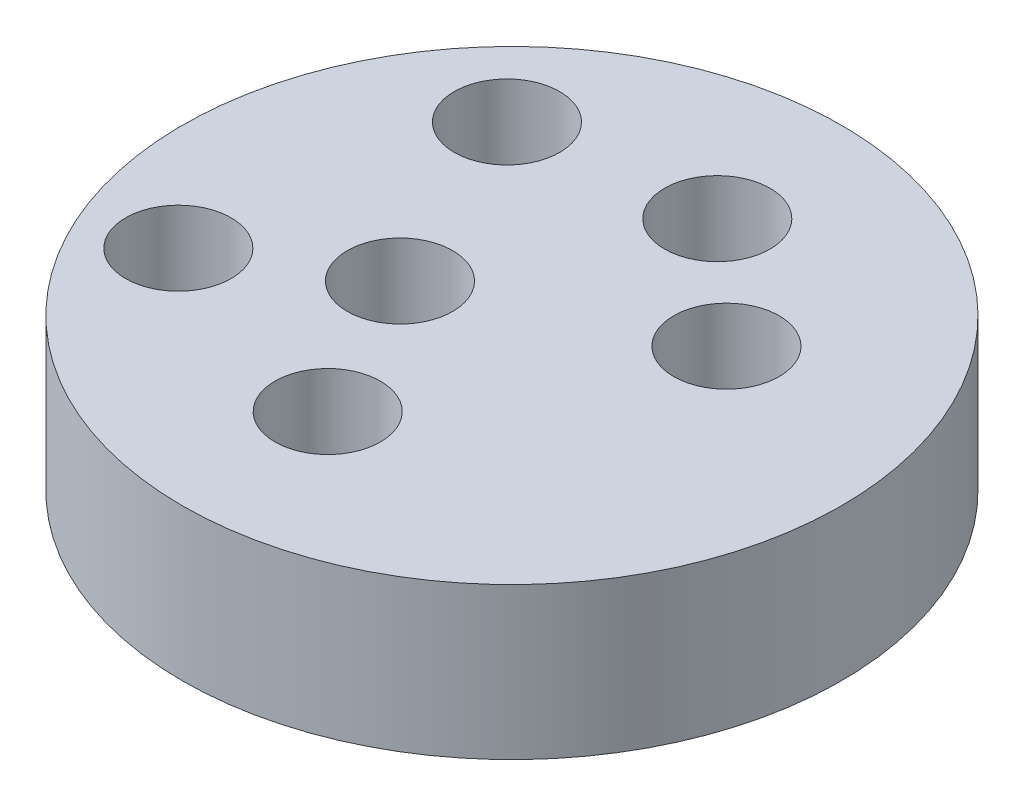
SolidWorks part; units mm, degrees
ref_plane "Front Plane" through (0, 0, 0) normal (0, 0, 1) x (1, 0, 0)
ref_plane "Top Plane" through (0, 0, 0) normal (0, 1, 0) x (1, 0, 0)
ref_plane "Right Plane" through (0, 0, 0) normal (1, 0, 0) x (0, 0, -1)
sketch "Sketch2" plane through (0, 0, 0) normal (0, 1, 0) x (1, 0, 0)
  circle A0 centre (0, 0) radius 50
  dimension "D1" = 100
extrude "Boss-Extrude2" add sketch "Sketch2" along normal blind 23
hole_wizard "Ø16.0mm Dowel Hole1" positions "Sketch5" profile "Sketch6" hole size "Ø16.0" standard "DIN" end condition through all
sketch "Sketch5" plane through (0, 23, 0) normal (0, 1, 0) x (1, 0, 0)
  point P0 (-34.1473, -16.4608)
  point P2 (-25.8045, 25.0499)
  point P4 (-1.359, -26.5937)
  point P6 (20.3005, 12.2433)
  point P8 (-13.0224, -3.961)
  point P10 (2.8526, 28.3026)
sketch "Sketch6" plane through (-34.1473, 23, 16.4608) normal (1, 0, 0) x (0, 0, 1)
  line L0 (0, 0) -> (0, 23)
  line L1 (0, 23) -> (8, 23)
  line L2 (8, 23) -> (8, 0)
  line L5 (8, 0) -> (0, 0)
  line L11 (0, -6.35) -> (0, 107.95) construction
  dimension "Thru Hole Dia." = 16
  dimension "Thru Hole Depth" = 23
